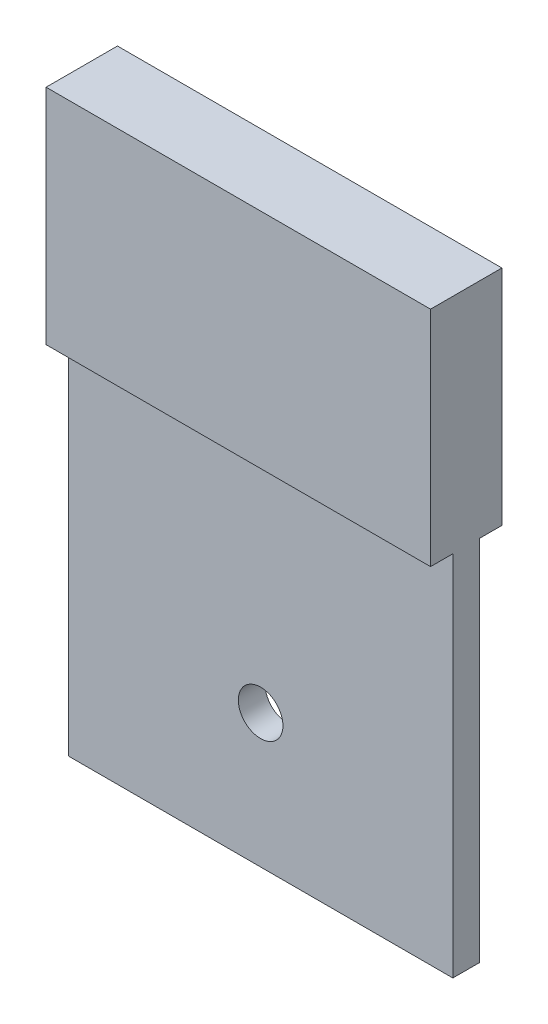
SolidWorks part; units mm, degrees
material "Pure Lead"
ref_plane "Front Plane" through (0, 0, 0) normal (0, 0, 1) x (1, 0, 0)
ref_plane "Top Plane" through (0, 0, 0) normal (0, 1, 0) x (1, 0, 0)
ref_plane "Right Plane" through (0, 0, 0) normal (1, 0, 0) x (0, 0, -1)
sketch "Sketch1" plane through (0, 0, 0) normal (0, 0, 1) x (1, 0, 0)
  line L1 (-97.1613, 63.9318) -> (-10.9592, 63.9318)
  line L2 (-97.1613, 63.9318) -> (-97.1613, -18.4502)
  line L3 (-97.1613, -18.4502) -> (-10.9592, -18.4502)
  line L4 (-10.9592, 63.9318) -> (-10.9592, -18.4502)
  circle A0 centre (-54.0602, 11.483) radius 5
  point P6 (-54.0602, -18.4502)
  dimension "D2" = 10
  dimension "D1" = 0
extrude "Boss-Extrude1" add sketch "Sketch1" along normal blind 6
sketch "Sketch2" plane through (0, 63.9318, 0) normal (0, 1, 0) x (1, 0, 0)
  line L0 (-97.1613, -6) -> (-97.1613, -11)
  line L1 (-97.1613, -11) -> (-10.9592, -11)
  line L2 (-10.9592, -11) -> (-10.9592, 5)
  line L3 (-10.9592, 5) -> (-97.1613, 5)
  line L4 (-97.1613, 5) -> (-97.1613, -6)
  line L5 (-10.9592, 0) -> (-97.1613, 0) construction
  line L6 (-10.9592, -6) -> (-97.1613, -6) construction
  dimension "D1" = 5
  dimension "D2" = 5
extrude "Boss-Extrude2" add sketch "Sketch2" along normal blind 50
